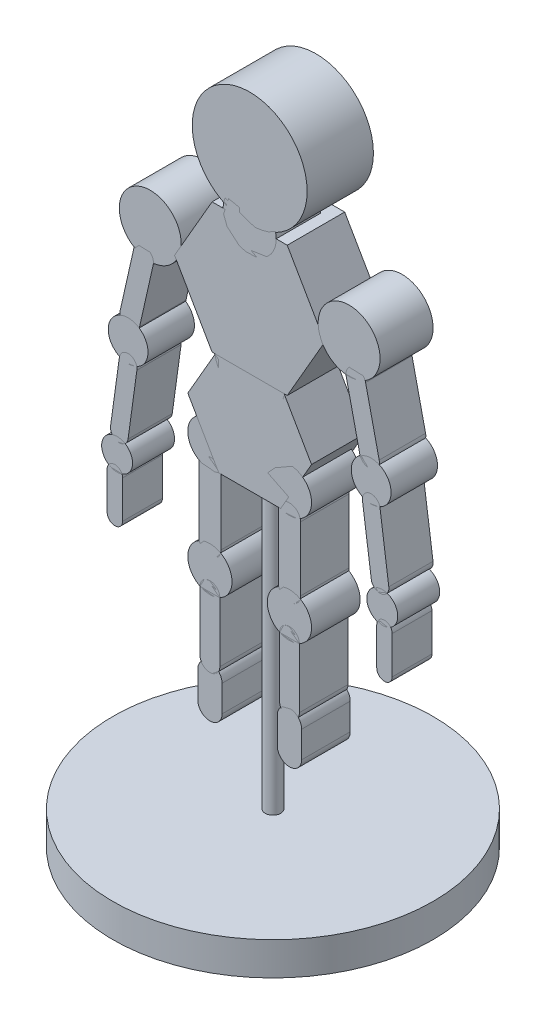
SolidWorks part; units mm, degrees
ref_plane "前视基准面" through (0, 0, 0) normal (0, 0, 1) x (1, 0, 0)
ref_plane "上视基准面" through (0, 0, 0) normal (0, 1, 0) x (1, 0, 0)
ref_plane "右视基准面" through (0, 0, 0) normal (1, 0, 0) x (0, 0, -1)
other "Configuration Table"
sketch "草图2" plane through (0, 0, 0) normal (0, 0, 1) x (1, 0, 0)
  line L0 (-18, -111) -> (-18, -99) construction
  line L1 (-23.5, -111) -> (-23.5, -99)
  line L2 (-12.5, -111) -> (-12.5, -99)
  arc A0 (-23.5, -111) -> (-12.5, -111) centre (-18, -111) ccw
  arc A1 (-12.5, -99) -> (-23.5, -99) centre (-18, -99) ccw
  point P2 (-18, -105)
extrude "凸台-拉伸2" add sketch "草图2" against normal blind 22 separate body
sketch "草图3" plane through (0, 0, 0) normal (0, 0, 1) x (1, 0, 0)
  line L0 (18, -111) -> (18, -99) construction
  line L1 (12.5, -111) -> (12.5, -99)
  line L2 (23.5, -111) -> (23.5, -99)
  arc A0 (12.5, -111) -> (23.5, -111) centre (18, -111) ccw
  arc A1 (23.5, -99) -> (12.5, -99) centre (18, -99) ccw
  point P2 (18, -105)
extrude "凸台-拉伸3" add sketch "草图3" against normal blind 22 separate body
sketch "草图4" plane through (0, 0, 0) normal (0, 0, 1) x (1, 0, 0)
  line L0 (-18, -93) -> (-18, -66) construction
  line L1 (-22.5, -93) -> (-22.5, -66)
  line L2 (-13.5, -93) -> (-13.5, -66)
  arc A0 (-22.5, -93) -> (-13.5, -93) centre (-18, -93) ccw
  arc A1 (-13.5, -66) -> (-22.5, -66) centre (-18, -66) ccw
  point P2 (-18, -79.5)
extrude "凸台-拉伸4" add sketch "草图4" against normal blind 22 separate body
sketch "草图5" plane through (0, 0, 0) normal (0, 0, 1) x (1, 0, 0)
  circle A0 centre (-18, -57) radius 10
extrude "凸台-拉伸5" add sketch "草图5" against normal blind 22 separate body
sketch "草图6" plane through (0, 0, 0) normal (0, 0, 1) x (1, 0, 0)
  line L0 (-18, -47) -> (-18, -18) construction
  line L1 (-23, -47) -> (-23, -18)
  line L2 (-13, -47) -> (-13, -18)
  circle A0 centre (-18, -57) radius 10 construction
  arc A1 (-23, -47) -> (-13, -47) centre (-18, -47) ccw
  arc A2 (-13, -18) -> (-23, -18) centre (-18, -18) ccw
  point P5 (-18, -32.5)
extrude "凸台-拉伸6" add sketch "草图6" against normal blind 22 separate body
sketch "草图7" plane through (0, 0, 0) normal (0, 0, 1) x (1, 0, 0)
  circle A0 centre (-18, -8) radius 10
extrude "凸台-拉伸7" add sketch "草图7" against normal blind 22 separate body
sketch "草图8" plane through (0, 0, 0) normal (0, 0, 1) x (1, 0, 0)
  line L0 (18, -93) -> (18, -66) construction
  line L1 (13.5, -93) -> (13.5, -66)
  line L2 (22.5, -93) -> (22.5, -66)
  arc A0 (13.5, -93) -> (22.5, -93) centre (18, -93) ccw
  arc A1 (22.5, -66) -> (13.5, -66) centre (18, -66) ccw
  point P2 (18, -79.5)
extrude "凸台-拉伸8" add sketch "草图8" against normal blind 22 separate body
sketch "草图9" plane through (0, 0, 0) normal (0, 0, 1) x (1, 0, 0)
  circle A0 centre (18, -57) radius 10
extrude "凸台-拉伸9" add sketch "草图9" against normal blind 22 separate body
sketch "草图10" plane through (0, 0, 0) normal (0, 0, 1) x (1, 0, 0)
  line L0 (18, -47) -> (18, -18) construction
  line L1 (13, -47) -> (13, -18)
  line L2 (23, -47) -> (23, -18)
  circle A0 centre (18, -57) radius 10 construction
  arc A1 (13, -47) -> (23, -47) centre (18, -47) ccw
  arc A2 (23, -18) -> (13, -18) centre (18, -18) ccw
  point P5 (18, -32.5)
extrude "凸台-拉伸10" add sketch "草图10" against normal blind 22 separate body
sketch "草图11" plane through (0, 0, 0) normal (0, 0, 1) x (1, 0, 0)
  circle A0 centre (18, -8) radius 10
extrude "凸台-拉伸11" add sketch "草图11" against normal blind 22 separate body
sketch "草图12" plane through (0, 0, 0) normal (0, 0, 1) x (1, 0, 0)
  line L1 (28, 7) -> (14, 31.2487)
  line L2 (14, 31.2487) -> (-14, 31.2487)
  line L3 (-14, 31.2487) -> (-28, 7)
  line L4 (-28, 7) -> (-14, -17.2487)
  line L5 (-14, -17.2487) -> (14, -17.2487)
  line L6 (14, -17.2487) -> (28, 7)
  circle A0 centre (0, 7) radius 24.2487 construction
extrude "凸台-拉伸12" add sketch "草图12" against normal blind 24 separate body
sketch "草图13" plane through (0, 0, 0) normal (0, 0, 1) x (1, 0, 0)
  line L0 (14, 31.2487) -> (-14, 31.2487) construction
  circle A0 centre (0, 31.2487) radius 16
extrude "凸台-拉伸13" add sketch "草图13" against normal blind 22 separate body
sketch "草图14" plane through (0, 0, 0) normal (0, 0, 1) x (1, 0, 0)
  line L1 (34, 58) -> (17, 87.4449)
  line L2 (17, 87.4449) -> (-17, 87.4449)
  line L3 (-17, 87.4449) -> (-34, 58)
  line L4 (-34, 58) -> (-17, 28.5551)
  line L5 (-17, 28.5551) -> (17, 28.5551)
  line L6 (17, 28.5551) -> (34, 58)
  circle A0 centre (0, 58) radius 29.4449 construction
extrude "凸台-拉伸14" add sketch "草图14" against normal blind 26 separate body
sketch "草图15" plane through (0, 0, 0) normal (0, 0, 1) x (1, 0, 0)
  line L0 (17, 87.4449) -> (-17, 87.4449) construction
  circle A0 centre (0, 87.4449) radius 12
extrude "凸台-拉伸15" add sketch "草图15" against normal blind 20 separate body
sketch "草图16" plane through (0, 0, 0) normal (0, 0, 1) x (1, 0, 0)
  circle A0 centre (0, 113) radius 26
extrude "凸台-拉伸16" add sketch "草图16" against normal blind 30 separate body
sketch "草图17" plane through (0, 0, 0) normal (0, 0, 1) x (1, 0, 0)
  circle A0 centre (-45, 64) radius 14
extrude "凸台-拉伸17" add sketch "草图17" against normal blind 24 separate body
sketch "草图18" plane through (0, 0, 0) normal (0, 0, 1) x (1, 0, 0)
  line L0 (-48.0732, 50.3415) -> (-54.2142, 23.0482) construction
  line L1 (-43.6829, 49.3537) -> (-49.8239, 22.0604)
  line L2 (-52.4634, 51.3293) -> (-58.6044, 24.036)
  circle A0 centre (-45, 64) radius 14 construction
  arc A1 (-43.6829, 49.3537) -> (-52.4634, 51.3293) centre (-48.0732, 50.3415) ccw
  arc A2 (-58.6044, 24.036) -> (-49.8239, 22.0604) centre (-54.2142, 23.0482) ccw
  point P4 (-51.1437, 36.6948)
extrude "凸台-拉伸18" add sketch "草图18" against normal blind 21 separate body
sketch "草图19" plane through (0, 0, 0) normal (0, 0, 1) x (1, 0, 0)
  circle A0 centre (-55, 14) radius 9
extrude "凸台-拉伸19" add sketch "草图19" against normal blind 21 separate body
sketch "草图20" plane through (0, 0, 0) normal (0, 0, 1) x (1, 0, 0)
  line L0 (-55, 5) -> (-59, -24) construction
  line L1 (-51.0375, 4.4535) -> (-55.0375, -24.5465)
  line L2 (-58.9625, 5.5465) -> (-62.9625, -23.4535)
  circle A0 centre (-55, 14) radius 9 construction
  arc A1 (-51.0375, 4.4535) -> (-58.9625, 5.5465) centre (-55, 5) ccw
  arc A2 (-62.9625, -23.4535) -> (-55.0375, -24.5465) centre (-59, -24) ccw
  point P4 (-57, -9.5)
extrude "凸台-拉伸20" add sketch "草图20" against normal blind 20 separate body
sketch "草图21" plane through (0, 0, 0) normal (0, 0, 1) x (1, 0, 0)
  circle A0 centre (-60, -33) radius 7
extrude "凸台-拉伸21" add sketch "草图21" against normal blind 19 separate body
sketch "草图22" plane through (0, 0, 0) normal (0, 0, 1) x (1, 0, 0)
  line L0 (-61, -41) -> (-61, -58) construction
  line L1 (-57.5, -41) -> (-57.5, -58)
  line L2 (-64.5, -41) -> (-64.5, -58)
  arc A0 (-57.5, -41) -> (-64.5, -41) centre (-61, -41) ccw
  arc A1 (-64.5, -58) -> (-57.5, -58) centre (-61, -58) ccw
  point P2 (-61, -49.5)
extrude "凸台-拉伸22" add sketch "草图22" against normal blind 18 separate body
sketch "草图23" plane through (0, 0, 0) normal (0, 0, 1) x (1, 0, 0)
  circle A0 centre (45, 64) radius 14
extrude "凸台-拉伸23" add sketch "草图23" against normal blind 24 separate body
sketch "草图24" plane through (0, 0, 0) normal (0, 0, 1) x (1, 0, 0)
  line L0 (48.0732, 50.3415) -> (54.2142, 23.0482) construction
  line L1 (52.4634, 51.3293) -> (58.6044, 24.036)
  line L2 (43.6829, 49.3537) -> (49.8239, 22.0604)
  circle A0 centre (45, 64) radius 14 construction
  arc A1 (52.4634, 51.3293) -> (43.6829, 49.3537) centre (48.0732, 50.3415) ccw
  arc A2 (49.8239, 22.0604) -> (58.6044, 24.036) centre (54.2142, 23.0482) ccw
  point P4 (51.1437, 36.6948)
extrude "凸台-拉伸24" add sketch "草图24" against normal blind 21 separate body
sketch "草图25" plane through (0, 0, 0) normal (0, 0, 1) x (1, 0, 0)
  circle A0 centre (55, 14) radius 9
extrude "凸台-拉伸25" add sketch "草图25" against normal blind 21 separate body
sketch "草图26" plane through (0, 0, 0) normal (0, 0, 1) x (1, 0, 0)
  line L0 (55, 5) -> (59, -24) construction
  line L1 (58.9625, 5.5465) -> (62.9625, -23.4535)
  line L2 (51.0375, 4.4535) -> (55.0375, -24.5465)
  circle A0 centre (55, 14) radius 9 construction
  arc A1 (58.9625, 5.5465) -> (51.0375, 4.4535) centre (55, 5) ccw
  arc A2 (55.0375, -24.5465) -> (62.9625, -23.4535) centre (59, -24) ccw
  point P4 (57, -9.5)
extrude "凸台-拉伸26" add sketch "草图26" against normal blind 20 separate body
sketch "草图27" plane through (0, 0, 0) normal (0, 0, 1) x (1, 0, 0)
  circle A0 centre (60, -33) radius 7
extrude "凸台-拉伸27" add sketch "草图27" against normal blind 19 separate body
sketch "草图28" plane through (0, 0, 0) normal (0, 0, 1) x (1, 0, 0)
  line L0 (61, -41) -> (61, -58) construction
  line L1 (64.5, -41) -> (64.5, -58)
  line L2 (57.5, -41) -> (57.5, -58)
  arc A0 (64.5, -41) -> (57.5, -41) centre (61, -41) ccw
  arc A1 (57.5, -58) -> (64.5, -58) centre (61, -58) ccw
  point P2 (61, -49.5)
extrude "凸台-拉伸28" add sketch "草图28" against normal blind 18 separate body
sketch "草图29" plane through (0, -17.2487, 0) normal (0, -1, 0) x (1, 0, 0)
  circle A0 centre (0, -10.5286) radius 3.5
  dimension "D1" = 7
extrude "凸台-拉伸29" add sketch "草图29" along normal blind 130
sketch "草图30" plane through (0, -147.2487, 0) normal (0, -1, 0) x (1, 0, 0)
  circle A0 centre (0, -10.5286) radius 72.5
  dimension "D1" = 145
extrude "凸台-拉伸30" add sketch "草图30" along normal blind 15
